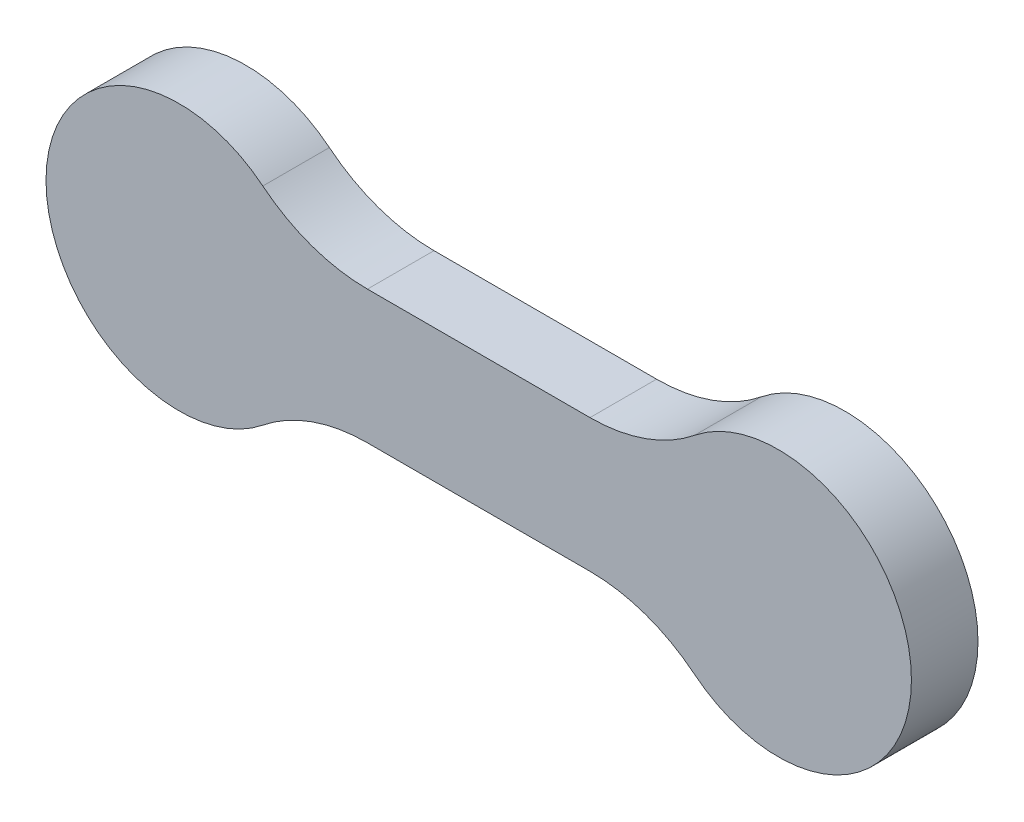
SolidWorks part; units mm, degrees
material "1060 合金"
ref_plane "前视基准面" through (0, 0, 0) normal (0, 0, 1) x (1, 0, 0)
ref_plane "上视基准面" through (0, 0, 0) normal (0, 1, 0) x (1, 0, 0)
ref_plane "右视基准面" through (0, 0, 0) normal (1, 0, 0) x (0, 0, -1)
sketch "草图1" plane through (0, 0, 0) normal (0, 0, 1) x (1, 0, 0)
  line L0 (56.5685, 20) -> (123.4315, 20)
  line L1 (56.5685, -20) -> (123.4315, -20)
  arc A0 (25.1416, 31.1111) -> (25.1416, -31.1111) centre (0, 0) ccw
  arc A1 (154.8584, -31.1111) -> (154.8584, 31.1111) centre (180, 0) ccw
  arc A2 (123.4315, 20) -> (154.8584, 31.1111) centre (123.4315, 70) ccw
  arc A3 (123.4315, -20) -> (154.8584, -31.1111) centre (123.4315, -70) cw
  arc A4 (56.5685, -20) -> (25.1416, -31.1111) centre (56.5685, -70) ccw
  arc A5 (56.5685, 20) -> (25.1416, 31.1111) centre (56.5685, 70) cw
  dimension "D1" = 80
  dimension "D2" = 80
  dimension "D6" = 50
  dimension "D3" = 180
  dimension "D4" = 20
  dimension "D5" = 20
extrude "凸台-拉伸1" add sketch "草图1" along normal blind 20
